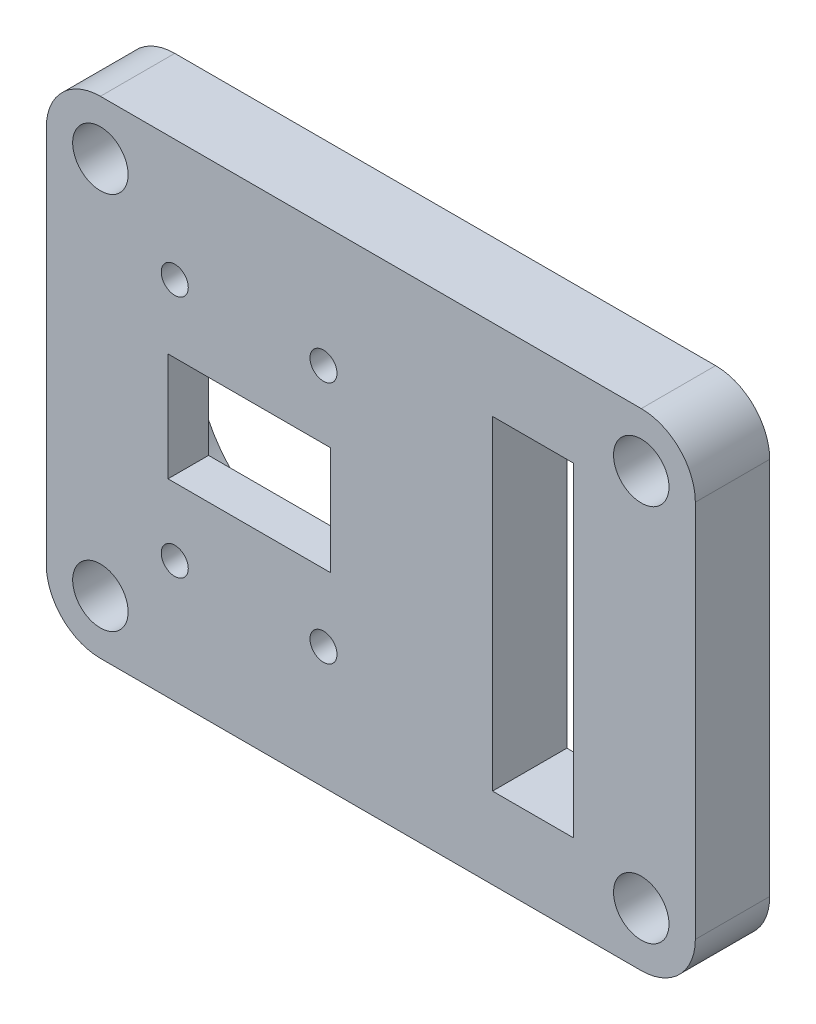
SolidWorks part; units mm, degrees
ref_plane "Front Plane" through (0, 0, 0) normal (0, 0, 1) x (1, 0, 0)
ref_plane "Top Plane" through (0, 0, 0) normal (0, 1, 0) x (1, 0, 0)
ref_plane "Right Plane" through (0, 0, 0) normal (1, 0, 0) x (0, 0, -1)
sketch "Sketch1" plane through (0, 0, 0) normal (0, 0, 1) x (1, 0, 0)
  line L1 (-20, -18) -> (20, -18)
  line L2 (-24, -14) -> (-24, 14)
  line L3 (-20, 18) -> (20, 18)
  line L4 (24, -14) -> (24, 14)
  line L5 (-24, -18) -> (24, 18) construction
  line L6 (-24, 18) -> (24, -18) construction
  arc A0 (-24, -14) -> (-20, -18) centre (-20, -14) ccw
  arc A1 (20, -18) -> (24, -14) centre (20, -14) ccw
  arc A2 (24, 14) -> (20, 18) centre (20, 14) ccw
  arc A3 (-20, 18) -> (-24, 14) centre (-20, 14) ccw
  circle A4 centre (-20, -14) radius 2.05
  circle A5 centre (-20, 14) radius 2.05
  circle A6 centre (20, 14) radius 2.05
  circle A7 centre (20, -14) radius 2.05
  point P0 (0, 0)
  dimension "D3" = 4
  dimension "D4" = 4
  dimension "D5" = 4
  dimension "D6" = 4
  dimension "D7" = 4.1
  dimension "D8" = 4.1
  dimension "D9" = 4.1
  dimension "D10" = 4.1
  dimension "D1" = 48
  dimension "D2" = 36
extrude "Boss-Extrude1" add sketch "Sketch1" along normal mid plane 5.5
sketch "Sketch2" plane through (0, 0, -2.75) normal (0, 0, 1) x (1, 0, 0)
  line L0 (-1000, 0) -> (49000, 0) construction
  line L1 (-9, -1000) -> (-9, 49000) construction
  circle A0 centre (-20, -14) radius 2.05 construction
  circle A1 centre (-9, 0) radius 9.5
  dimension "D2" = 19
  dimension "D1" = 11
extrude "Cut-Extrude1" cut sketch "Sketch2" along normal blind 2.5
sketch "Sketch3" plane through (0, 0, -0.25) normal (0, 0, -1) x (1, 0, 0)
  line L1 (-15, -4) -> (-3, -4)
  line L2 (-15, -4) -> (-15, 4)
  line L3 (-15, 4) -> (-3, 4)
  line L4 (-3, -4) -> (-3, 4)
  line L5 (-15, -4) -> (-3, 4) construction
  line L6 (-15, 4) -> (-3, -4) construction
  point P0 (-9, 0)
  dimension "D1" = 12
  dimension "D2" = 8
extrude "Cut-Extrude2" cut sketch "Sketch3" against normal through all
sketch "Sketch4" plane through (0, 0, 2.75) normal (0, 0, 1) x (1, 0, 0)
  line L0 (-1003, 0) -> (48997, 0) construction
  line L1 (-3, 4) -> (-3, -4) construction
  line L2 (-9, -996) -> (-9, 49004) construction
  line L3 (-15, 4) -> (-3, 4) construction
  line L5 (-3.5, -9) -> (-14.5, -9) construction
  line L6 (-3.5, -9) -> (-3.5, 9) construction
  line L7 (-3.5, 9) -> (-14.5, 9) construction
  line L8 (-14.5, -9) -> (-14.5, 9) construction
  line L9 (-3.5, -9) -> (-14.5, 9) construction
  line L10 (-3.5, 9) -> (-14.5, -9) construction
  circle A0 centre (-14.5, 9) radius 1
  circle A1 centre (-3.5, 9) radius 1
  circle A2 centre (-3.5, -9) radius 1
  circle A3 centre (-14.5, -9) radius 1
  point P5 (-3, 0)
  point P6 (-9, 0)
  point P10 (-9, 4)
  dimension "D3" = 2
  dimension "D4" = 2
  dimension "D5" = 2
  dimension "D6" = 2
  dimension "D1" = 11
  dimension "D2" = 18
extrude "Cut-Extrude3" cut sketch "Sketch4" against normal through all
sketch "Sketch5" plane through (0, 0, 2.75) normal (0, 0, 1) x (1, 0, 0)
  line L0 (-1000, 0) -> (49000, 0) construction
  line L1 (-15, 4) -> (-3, 4) construction
  line L2 (9, -12) -> (15, -12)
  line L3 (9, -12) -> (9, 12)
  line L4 (9, 12) -> (15, 12)
  line L5 (15, -12) -> (15, 12)
  line L6 (9, -12) -> (15, 12) construction
  line L7 (9, 12) -> (15, -12) construction
  point P1 (12, 0)
  point P8 (-9, 4)
  dimension "D1" = 6
  dimension "D2" = 24
  dimension "D3" = 21
extrude "Cut-Extrude4" cut sketch "Sketch5" against normal through all
